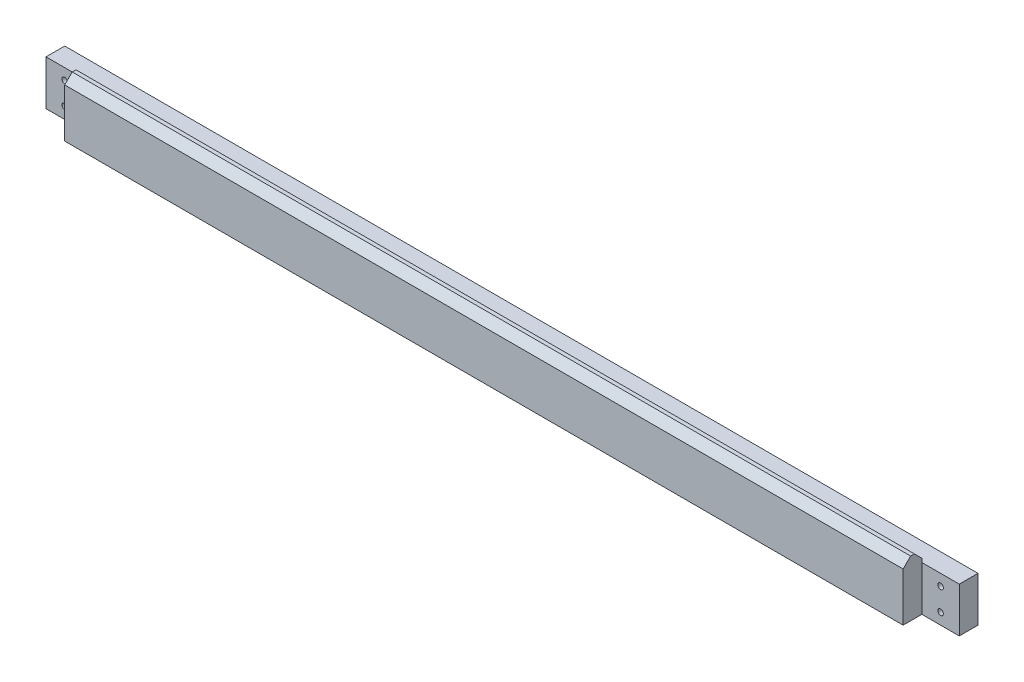
SolidWorks part; units mm, degrees
ref_plane "Front Plane" through (0, 0, 0) normal (0, 0, 1) x (1, 0, 0)
ref_plane "Top Plane" through (0, 0, 0) normal (0, 1, 0) x (1, 0, 0)
ref_plane "Right Plane" through (0, 0, 0) normal (1, 0, 0) x (0, 0, -1)
sketch "Sketch1" plane through (0, 0, 0) normal (0, 0, 1) x (1, 0, 0)
  line L1 (774.7, 38.1) -> (-774.7, 38.1)
  line L2 (774.7, 38.1) -> (774.7, -38.1)
  line L3 (774.7, -38.1) -> (-774.7, -38.1)
  line L4 (-774.7, 38.1) -> (-774.7, -38.1)
  line L5 (774.7, 38.1) -> (-774.7, -38.1) construction
  line L6 (774.7, -38.1) -> (-774.7, 38.1) construction
  point P0 (0, 0)
  dimension "D1" = 76.2
  dimension "D2" = 1549.4
extrude "Boss-Extrude1" add sketch "Sketch1" along normal blind 31.75
sketch "Sketch2" plane through (0, 0, 31.75) normal (0, 0, 1) x (1, 0, 0)
  line L0 (742.95, 38.1) -> (742.95, -38.1) construction
  line L1 (774.7, 38.1) -> (-774.7, 38.1) construction
  line L2 (-774.7, -38.1) -> (774.7, -38.1) construction
  line L3 (774.7, -38.1) -> (774.7, 38.1) construction
  circle A0 centre (742.95, 19.05) radius 4.7625
  circle A1 centre (742.95, -19.05) radius 4.7625
  dimension "D1" = 19.05
  dimension "D2" = 19.05
  dimension "D3" = 9.525
  dimension "D4" = 31.75
extrude "Cut-Extrude1" cut sketch "Sketch2" against normal through all
mirror "Mirror1" about plane through (0, 0, 0) normal (1, 0, 0) of "Cut-Extrude1"
sketch "Sketch3" plane through (0, 0, 31.75) normal (0, 0, 1) x (1, 0, 0)
  line L0 (0, -62.7332) -> (0, 50.5728) construction
  line L1 (-774.7, -38.1) -> (774.7, -38.1) construction
  line L2 (711.2, 57.15) -> (-711.2, 57.15)
  line L3 (711.2, 57.15) -> (711.2, -38.1)
  line L4 (711.2, -38.1) -> (-711.2, -38.1)
  line L5 (-711.2, 57.15) -> (-711.2, -38.1)
  line L6 (711.2, 57.15) -> (-711.2, -38.1) construction
  line L7 (711.2, -38.1) -> (-711.2, 57.15) construction
  point P1 (0, 9.525)
  dimension "D1" = 95.25
  dimension "D2" = 1422.4
extrude "Boss-Extrude2" add sketch "Sketch3" along normal blind 31.75 contours L5 L4 L3 L2
chamfer "Chamfer1" distance 12.7 angle 45 2 edges at (0, 57.15, 31.75) (0, 57.15, 63.5)
